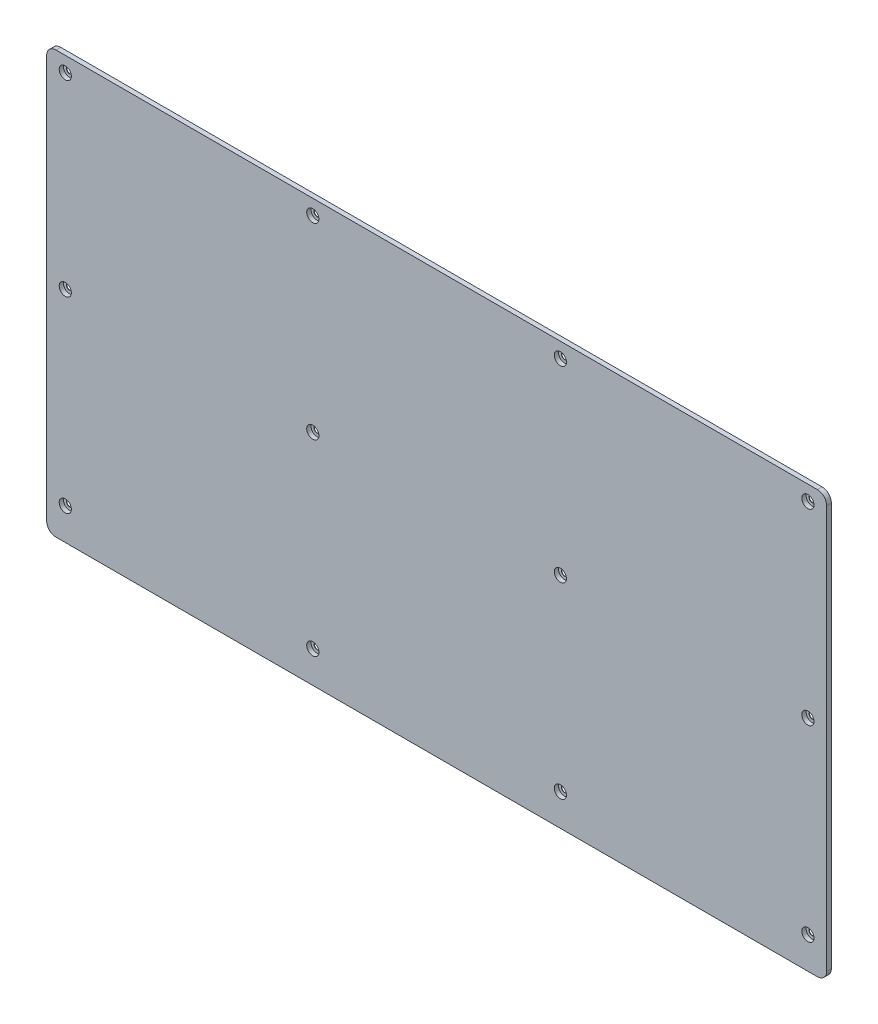
SolidWorks part; units mm, degrees
ref_plane "Plan de face" through (0, 0, 0) normal (0, 0, 1) x (1, 0, 0)
ref_plane "Plan de dessus" through (0, 0, 0) normal (0, 1, 0) x (1, 0, 0)
ref_plane "Plan de droite" through (0, 0, 0) normal (1, 0, 0) x (0, 0, -1)
sketch "Esquisse1" plane through (0, 0, 0) normal (0, 0, 1) x (1, 0, 0)
  line L1 (-406, -225) -> (406, -225)
  line L2 (-416, -215) -> (-416, 215)
  line L3 (-406, 225) -> (406, 225)
  line L4 (416, -215) -> (416, 215)
  line L5 (-416, -225) -> (416, 225) construction
  line L6 (-416, 225) -> (416, -225) construction
  arc A0 (416, 215) -> (406, 225) centre (406, 215) ccw
  arc A1 (406, -225) -> (416, -215) centre (406, -215) ccw
  arc A2 (-406, -225) -> (-416, -215) centre (-406, -215) cw
  arc A3 (-416, 215) -> (-406, 225) centre (-406, 215) cw
  point P0 (0, 0)
  dimension "D3" = 10
  dimension "D1" = 832
  dimension "D2" = 450
extrude "Boss.-Extru.1" add sketch "Esquisse1" along normal blind 5
hole_wizard "Dégagement M61" positions "Esquisse3" profile "Esquisse2" hole size "M6" standard "JIS" end condition through all
sketch "Esquisse3" plane through (0, 0, 0) normal (0, 0, -1) x (-1, 0, 0)
  point P0 (-395.9198, 208.8724)
sketch "Esquisse2" plane through (395.9198, 208.8724, 0) normal (1, 0, 0) x (0, 1, 0)
  line L0 (0, 0) -> (0, 5)
  line L1 (0, 5) -> (3.3, 5)
  line L2 (3.3, 5) -> (3.3, 0)
  line L5 (3.3, 0) -> (0, 0)
  line L11 (0, -6.35) -> (0, 107.95) construction
  dimension "Diamètre du perçage jusqu'au prochain" = 6.6
  dimension "Profondeur du perçage jusqu'au prochain" = 5
hole_wizard "Chambrage pour vis à tête ronde bombée M61" positions "Esquisse5" profile "Esquisse4" counterbore size "M6" standard "Ansi Metric" end condition through all
sketch "Esquisse5" plane through (0, 0, 5) normal (0, 0, 1) x (1, 0, 0)
  point P0 (395.9198, 208.8724)
sketch "Esquisse4" plane through (395.9198, 208.8724, 5) normal (1, 0, 0) x (0, -1, 0)
  line L0 (0, 0) -> (0, 5)
  line L1 (0, 5) -> (3.3, 5)
  line L2 (3.3, 4.625) -> (3.3, 5)
  line L3 (3.3, 4.625) -> (3.325, 4.6)
  line L4 (3.325, 4.6) -> (6.5, 4.6)
  line L5 (6.5, 4.6) -> (6.5, 0)
  line L7 (0, 0) -> (6.5, 0)
  line L9 (-3.3, 4.625) -> (-3.325, 4.6) construction
  line L11 (0, -6.35) -> (0, 107.95) construction
  dimension "Diamètre du perçage jusqu'au prochain" = 6.6
  dimension "Profondeur du perçage jusqu'au prochain" = 5
  dimension "Diamètre du chambrage" = 13
  dimension "Profondeur du chambrage" = 4.6
  dimension "Diamètre du fraisage milieu" = 6.65
  dimension "Angle du fraisage milieu" = 90
pattern_linear "Répétition linéaire1" count 5 spacing 100 along (0, -1, 0) count 4 spacing 264 along (-1, 0, 0) skipping (1, 0), (1, 1), (1, 2), (1, 3), (3, 0), (3, 1), (3, 2), (3, 3) of "Chambrage pour vis à tête ronde bombée M61"
